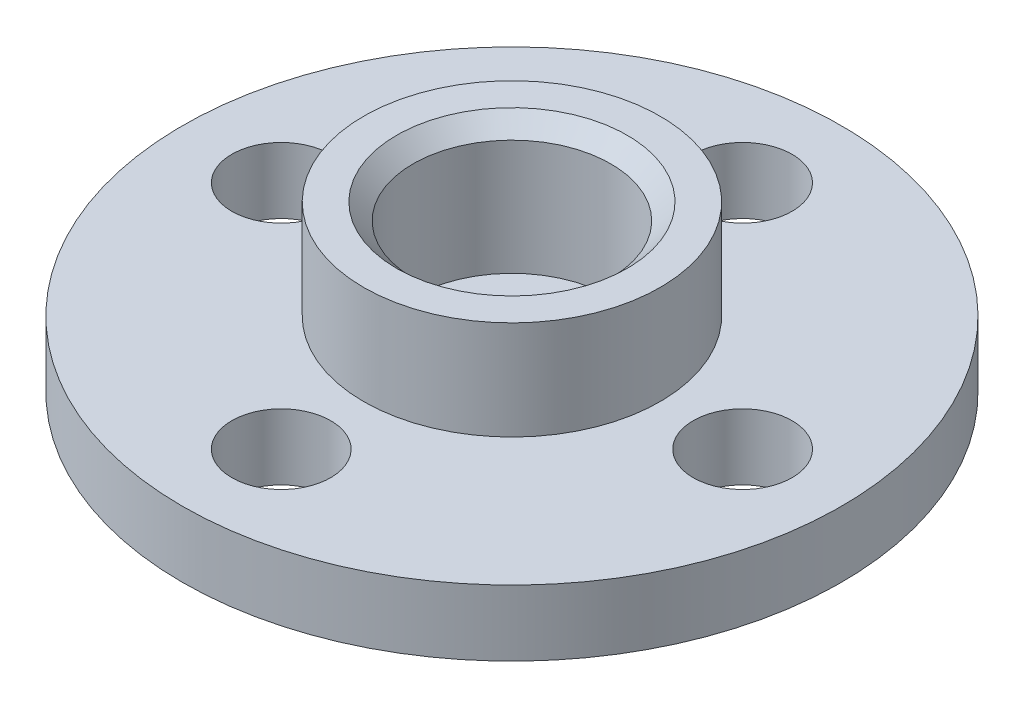
SolidWorks part; units mm, degrees
ref_plane "前视基准面" through (0, 0, 0) normal (0, 0, 1) x (1, 0, 0)
ref_plane "上视基准面" through (0, 0, 0) normal (0, 1, 0) x (1, 0, 0)
ref_plane "右视基准面" through (0, 0, 0) normal (1, 0, 0) x (0, 0, -1)
sketch "草图1" plane through (0, 0, 0) normal (0, 1, 0) x (1, 0, 0)
  circle A0 centre (0, 0) radius 10
extrude "凸台-拉伸1" add sketch "草图1" along normal blind 2
sketch "草图2" plane through (0, 2, 0) normal (0, 1, 0) x (1, 0, 0)
  circle A0 centre (0, 0) radius 4.5
extrude "凸台-拉伸2" add sketch "草图2" along normal blind 3
sketch "草图3" plane through (0, 2, 0) normal (0, 1, 0) x (1, 0, 0)
  circle A0 centre (-7, 0) radius 1.5
  circle A1 centre (0, 7) radius 1.5
  circle A2 centre (7, 0) radius 1.5
  circle A3 centre (0, -7) radius 1.5
  point P12 (0, 0)
  dimension "D1" = 4
extrude "切除-拉伸1" cut sketch "草图3" against normal blind 3
sketch "草图4" plane through (0, 5, 0) normal (0, 1, 0) x (1, 0, 0)
  circle A0 centre (0, 0) radius 3
extrude "切除-拉伸2" cut sketch "草图4" against normal blind 4
sketch "草图5" plane through (0, 1, 0) normal (0, 1, 0) x (1, 0, 0)
  circle A0 centre (0, 0) radius 1.5
extrude "切除-拉伸3" cut sketch "草图5" against normal blind 4
chamfer "倒角2" distance 0.5 angle 45 1 edges at (0, 5, 3)
